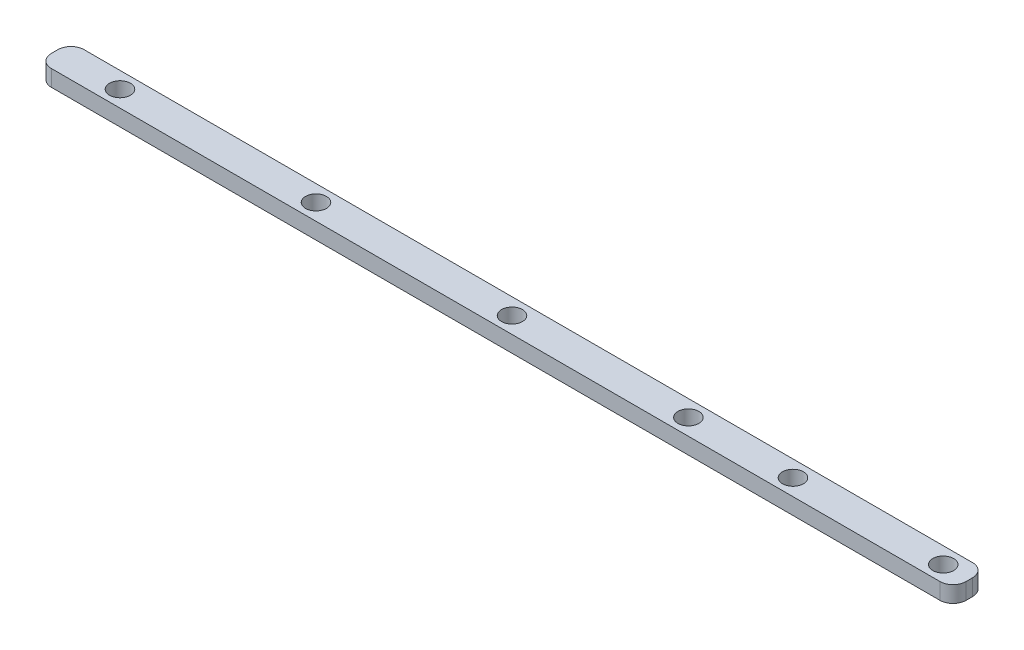
SolidWorks part; units mm, degrees
ref_plane "Front Plane" through (0, 0, 0) normal (0, 0, 1) x (1, 0, 0)
ref_plane "Top Plane" through (0, 0, 0) normal (0, 1, 0) x (1, 0, 0)
ref_plane "Right Plane" through (0, 0, 0) normal (1, 0, 0) x (0, 0, -1)
sketch "Sketch1" plane through (0, 0, 0) normal (0, 1, 0) x (1, 0, 0)
  line L1 (-88.9, -3.175) -> (88.9, -3.175)
  line L2 (-88.9, -3.175) -> (-88.9, 3.175)
  line L3 (-88.9, 3.175) -> (88.9, 3.175)
  line L4 (88.9, -3.175) -> (88.9, 3.175)
  line L5 (-88.9, -3.175) -> (88.9, 3.175) construction
  line L6 (-88.9, 3.175) -> (88.9, -3.175) construction
  point P0 (0, 0)
  dimension "D1" = 177.8
  dimension "D2" = 6.35
extrude "Boss-Extrude1" add sketch "Sketch1" along normal blind 3.175 contours L2 L3 L4 L1
fillet "Fillet1" radius 2.54 4 edges at (88.9, 1.5875, -3.175) (88.9, 1.5875, 3.175) (-88.9, 1.5875, 3.175) (-88.9, 1.5875, -3.175)
sketch "Sketch2" plane through (0, 3.175, 0) normal (0, 1, 0) x (1, 0, 0)
  line L0 (-88.9, 0) -> (88.9, 0) construction
  line L1 (-88.9, -0.635) -> (-88.9, 0.635) construction
  line L2 (88.9, -0.635) -> (88.9, 0.635) construction
  circle A0 centre (-76.2, 0) radius 2.032
  circle A1 centre (0, 0) radius 2.032
  circle A2 centre (-38.1, 0) radius 2.032
  circle A3 centre (83.82, 0) radius 2.032
  circle A4 centre (54.61, 0) radius 2.032
  circle A5 centre (34.29, 0) radius 2.032
  dimension "D1" = 4.064
  dimension "D2" = 5.08
  dimension "D3" = 34.29
  dimension "D4" = 38.1
  dimension "D5" = 76.2
  dimension "D6" = 34.29
extrude "Cut-Extrude1" cut sketch "Sketch2" against normal up to next
